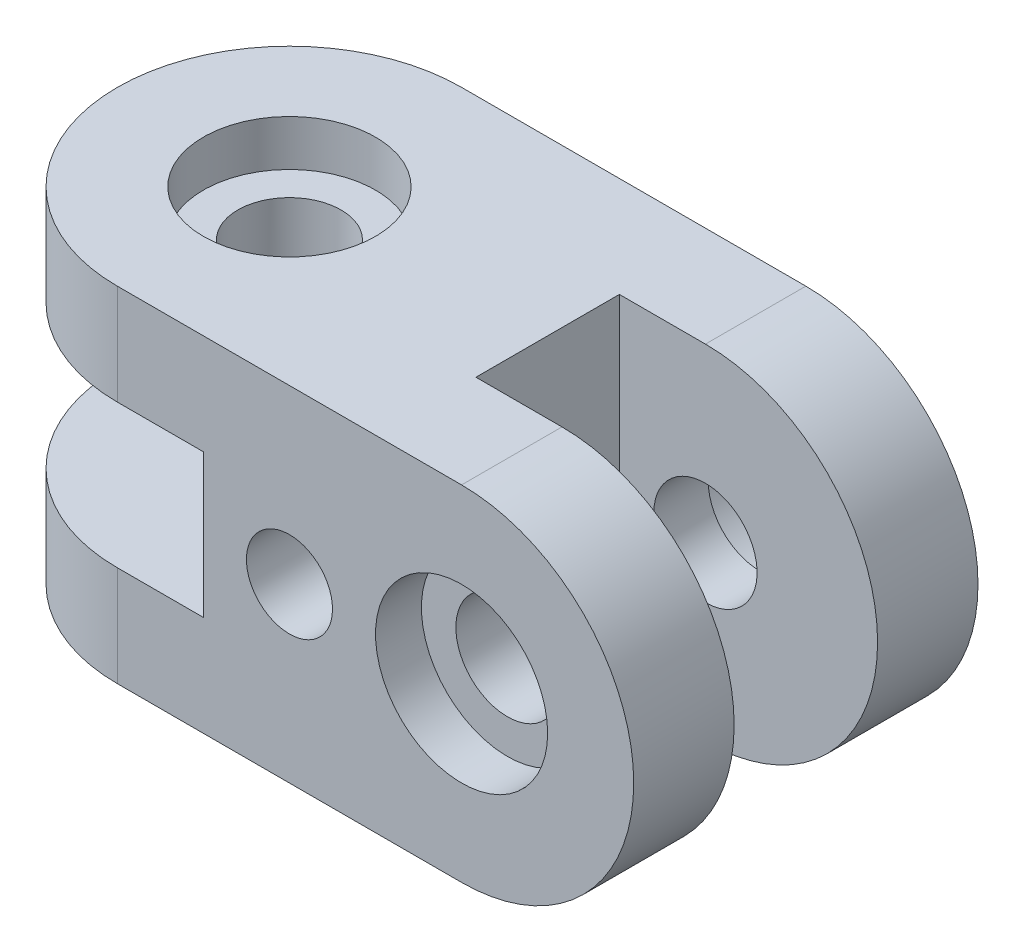
SolidWorks part; units mm, degrees
ref_plane "Front Plane" through (0, 0, 0) normal (0, 0, 1) x (1, 0, 0)
ref_plane "Top Plane" through (0, 0, 0) normal (0, 1, 0) x (1, 0, 0)
ref_plane "Right Plane" through (0, 0, 0) normal (1, 0, 0) x (0, 0, -1)
sketch "Sketch1" plane through (0, 0, 0) normal (0, 0, 1) x (1, 0, 0)
  line L0 (-60, 12.5) -> (-60, 30)
  line L1 (-60, -30) -> (30, -30)
  line L2 (-60, -30) -> (-60, -12.5)
  line L3 (-60, 30) -> (30, 30)
  line L5 (-60, -30) -> (60, 30) construction
  line L6 (-60, 30) -> (60, -30) construction
  line L7 (-15, -12.5) -> (-60, -12.5)
  line L8 (-15, -12.5) -> (-15, 12.5)
  line L9 (-15, 12.5) -> (-60, 12.5)
  line L11 (-15, -12.5) -> (-60, 12.5) construction
  line L12 (-15, 12.5) -> (-60, -12.5) construction
  arc A0 (30, 30) -> (30, -30) centre (30, 0) cw
  point P0 (0, 0)
  point P10 (-37.5, 0)
  dimension "D3" = 30
  dimension "D1" = 120
  dimension "D2" = 60
  dimension "D4" = 25
  dimension "D5" = 45
extrude "Boss-Extrude1" add sketch "Sketch1" along normal mid plane 60
sketch "Sketch3" plane through (0, 0, 0) normal (0, 0, 1) x (1, 0, 0)
  circle A0 centre (0, 0) radius 7.5
  dimension "D1" = 15
extrude "Cut-Extrude1" cut sketch "Sketch3" against normal through all both and the other way through all
sketch "Sketch4" plane through (0, 30, 0) normal (0, 1, 0) x (1, 0, 0)
  line L0 (30, 30) -> (-60, 30) construction
  line L1 (30, -30) -> (-60, -30) construction
  line L2 (-60, -30) -> (-60, 30) construction
  line L3 (-30, 30) -> (-30, 42.7706)
  line L4 (-30, 42.7706) -> (-70.4323, 42.7706)
  line L5 (-70.4323, 42.7706) -> (-70.4323, -35.7273)
  line L6 (-70.4323, -35.7273) -> (-30, -35.7273)
  line L7 (-30, -35.7273) -> (-30, -30)
  arc A0 (-30, 30) -> (-30, -30) centre (-30, 0) ccw
  dimension "D1" = 30
extrude "Cut-Extrude2" cut sketch "Sketch4" against normal through all both
sketch "Sketch5" plane through (0, 30, 0) normal (0, 1, 0) x (1, 0, 0)
  circle A0 centre (-30, 0) radius 15
  dimension "D1" = 30
extrude "Cut-Extrude3" cut sketch "Sketch5" against normal blind 8
sketch "Sketch6" plane through (0, 22, 0) normal (0, 1, 0) x (1, 0, 0)
  circle A0 centre (-30, 0) radius 9
  dimension "D1" = 18
extrude "Cut-Extrude4" cut sketch "Sketch6" against normal up to next
mirror "Mirror1" about plane through (0, 0, 0) normal (0, 1, 0) of "Cut-Extrude4", "Cut-Extrude3"
sketch "Sketch7" plane through (0, 0, 0) normal (0, 1, 0) x (1, 0, 0)
  line L0 (60, -30) -> (60, 30) construction
  line L1 (15, -12.5) -> (60, -12.5)
  line L2 (15, -12.5) -> (15, 12.5)
  line L3 (15, 12.5) -> (60, 12.5)
  line L4 (60, -12.5) -> (60, 12.5)
  line L5 (15, -12.5) -> (60, 12.5) construction
  line L6 (15, 12.5) -> (60, -12.5) construction
  point P0 (37.5, 0)
  point P5 (0, 0)
  dimension "D1" = 25
  dimension "D2" = 45
extrude "Cut-Extrude5" cut sketch "Sketch7" against normal through all both and the other way through all
sketch "Sketch8" plane through (0, 0, 30) normal (0, 0, 1) x (1, 0, 0)
  circle A0 centre (30, 0) radius 15
  arc A1 (30, -30) -> (30, 30) centre (30, 0) ccw construction
  dimension "D1" = 30
extrude "Cut-Extrude6" cut sketch "Sketch8" against normal blind 8
sketch "Sketch9" plane through (0, 0, 22) normal (0, 0, 1) x (1, 0, 0)
  circle A0 centre (30, 0) radius 9
  dimension "D1" = 18
extrude "Cut-Extrude7" cut sketch "Sketch9" against normal up to next
mirror "Mirror2" about plane through (0, 0, 0) normal (0, 0, 1) of "Cut-Extrude6", "Cut-Extrude7"
